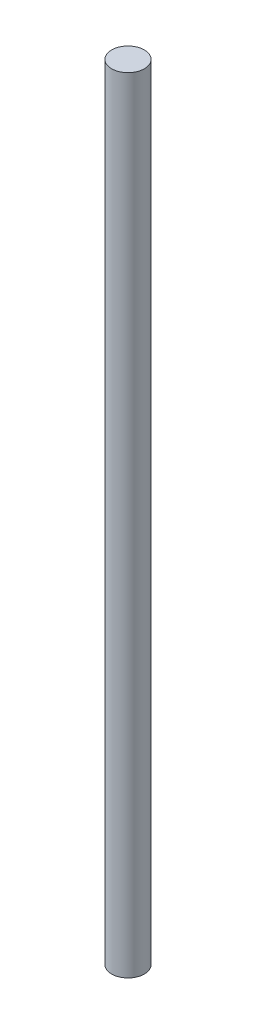
SolidWorks part; units mm, degrees
ref_plane "Front Plane" through (0, 0, 0) normal (0, 0, 1) x (1, 0, 0)
ref_plane "Top Plane" through (0, 0, 0) normal (0, 1, 0) x (1, 0, 0)
ref_plane "Right Plane" through (0, 0, 0) normal (1, 0, 0) x (0, 0, -1)
sketch "Sketch2" plane through (0, 0, 0) normal (0, 1, 0) x (1, 0, 0)
  circle A0 centre (0, 0) radius 1.25
  dimension "D1" = 2.5
extrude "Boss-Extrude1" add sketch "Sketch2" along normal blind 60
